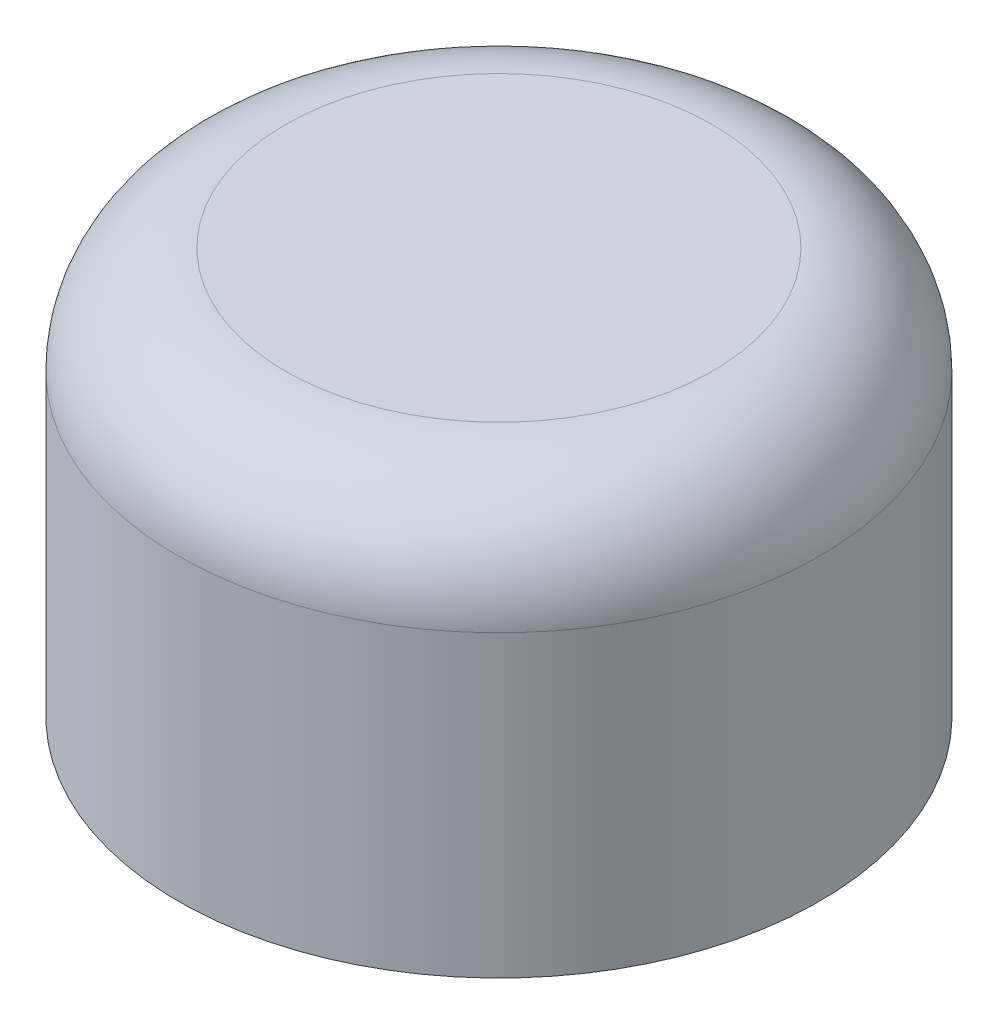
SolidWorks part; units mm, degrees
material "ABS"
ref_plane "正面" through (0, 0, 0) normal (0, 0, 1) x (1, 0, 0)
ref_plane "平面" through (0, 0, 0) normal (0, 1, 0) x (1, 0, 0)
ref_plane "右側面" through (0, 0, 0) normal (1, 0, 0) x (0, 0, -1)
sketch "ｽｹｯﾁ1" plane through (0, 0, 0) normal (0, 0, 1) x (1, 0, 0)
  line L1 (0, 20) -> (10, 20)
  line L3 (15, 15) -> (15, 1)
  line L4 (15, 1) -> (13, 1)
  line L5 (13, 1) -> (13, 3.5)
  line L7 (0, 20) -> (0, 18)
  line L8 (0, 18) -> (10, 18)
  line L9 (13, 3.5) -> (0, 3.5)
  line L10 (0, 3.5) -> (0, 6.5)
  line L11 (0, 6.5) -> (13, 6.5)
  line L12 (13, 6.5) -> (13, 15)
  line L13 (8, 0) -> (8, 4.2574) construction
  arc A0 (10, 20) -> (15, 15) centre (10, 15) cw
  arc A2 (10, 18) -> (13, 15) centre (10, 15) cw
  dimension "D4" = 20
  dimension "D7" = 8
  dimension "D1" = 19
  dimension "D2" = 10
  dimension "D3" = 2
  dimension "D5" = 15
  dimension "D6" = 2
  dimension "D8" = 3.5
  dimension "D9" = 3
revolve "回転1" add sketch "ｽｹｯﾁ1" angle 360 about L10
